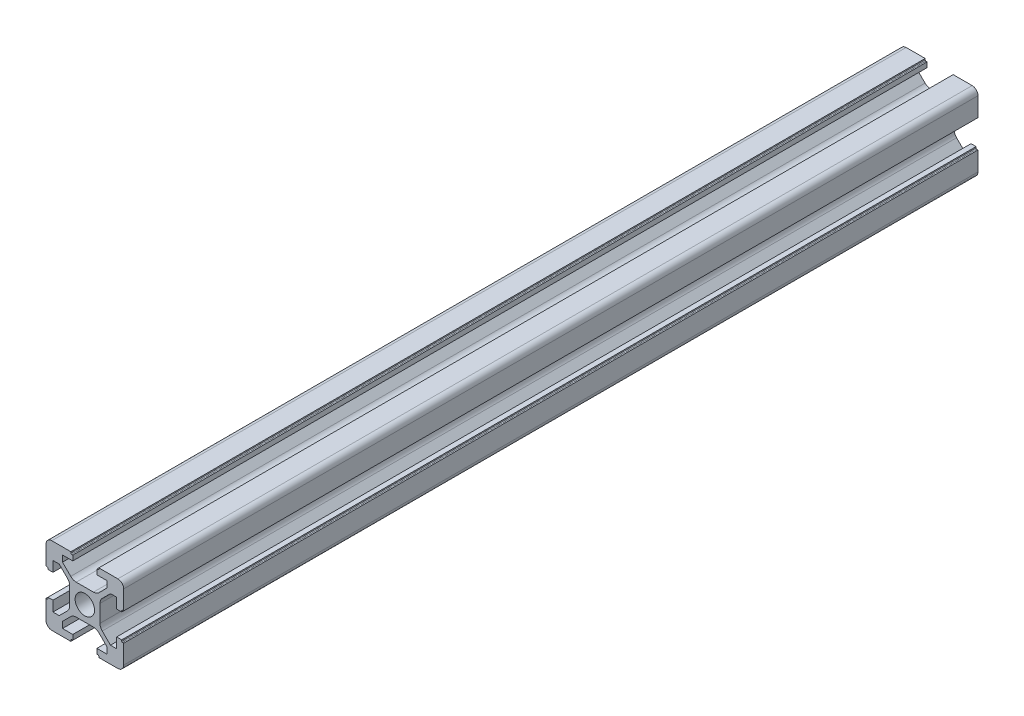
SolidWorks part; units mm, degrees
ref_plane "Alzado" through (0, 0, 0) normal (0, 0, 1) x (1, 0, 0)
ref_plane "Planta" through (0, 0, 0) normal (0, 1, 0) x (1, 0, 0)
ref_plane "Vista lateral" through (0, 0, 0) normal (1, 0, 0) x (0, 0, -1)
sketch "Croquis1" plane through (0, 0, 0) normal (0, 0, 1) x (1, 0, 0)
  line L0 (0, 0) -> (-10, -10) construction
  line L32 (0, 0) -> (-3.9, 0) construction
  line L58 (0, 0) -> (0, -3.9) construction
  line L60 (-4.4858, -3.6373) -> (-6.6, -5.7515)
  line L61 (-6.6, -5.7515) -> (-8.2, -5.7515)
  line L110 (-8.2, -5.7515) -> (-8.2, -3.1)
  line L111 (-8.2, -3.1) -> (-9.5, -3.1)
  line L112 (-9.5, -3.1) -> (-9.5, -3.4)
  line L113 (-9.7, -3.6) -> (-10, -3.6)
  line L114 (-10, -3.6) -> (-10, -8.5)
  line L115 (-3.6373, -4.4858) -> (-5.7515, -6.6)
  line L116 (-5.7515, -6.6) -> (-5.7515, -8.2)
  line L117 (-3.1, -8.2) -> (-3.1, -9.5)
  line L118 (-5.7515, -8.2) -> (-3.1, -8.2)
  line L119 (-3.1, -9.5) -> (-3.4, -9.5)
  line L120 (-3.6, -9.7) -> (-3.6, -10)
  line L121 (-3.6, -10) -> (-8.5, -10)
  line L122 (9.7, -3.6) -> (10, -3.6)
  line L123 (9.5, -3.1) -> (9.5, -3.4)
  line L124 (8.2, -3.1) -> (9.5, -3.1)
  line L125 (3.6, -10) -> (8.5, -10)
  line L126 (3.6, -9.7) -> (3.6, -10)
  line L127 (3.1, -9.5) -> (3.4, -9.5)
  line L128 (5.7515, -8.2) -> (3.1, -8.2)
  line L129 (3.1, -8.2) -> (3.1, -9.5)
  line L130 (5.7515, -6.6) -> (5.7515, -8.2)
  line L131 (3.6373, -4.4858) -> (5.7515, -6.6)
  line L132 (10, -3.6) -> (10, -8.5)
  line L133 (8.2, -5.7515) -> (8.2, -3.1)
  line L134 (6.6, -5.7515) -> (8.2, -5.7515)
  line L135 (4.4858, -3.6373) -> (6.6, -5.7515)
  line L136 (5.7515, 8.2) -> (3.1, 8.2)
  line L137 (3.6, 10) -> (8.5, 10)
  line L138 (-9.7, 3.6) -> (-10, 3.6)
  line L139 (-9.5, 3.1) -> (-9.5, 3.4)
  line L140 (-8.2, 3.1) -> (-9.5, 3.1)
  line L141 (-8.2, 5.7515) -> (-8.2, 3.1)
  line L142 (-6.6, 5.7515) -> (-8.2, 5.7515)
  line L143 (-4.4858, 3.6373) -> (-6.6, 5.7515)
  line L144 (3.1, 8.2) -> (3.1, 9.5)
  line L145 (3.1, 9.5) -> (3.4, 9.5)
  line L146 (3.6, 9.7) -> (3.6, 10)
  line L147 (-3.6, 10) -> (-8.5, 10)
  line L148 (-3.6, 9.7) -> (-3.6, 10)
  line L149 (-3.1, 9.5) -> (-3.4, 9.5)
  line L150 (-5.7515, 8.2) -> (-3.1, 8.2)
  line L151 (-3.1, 8.2) -> (-3.1, 9.5)
  line L152 (-5.7515, 6.6) -> (-5.7515, 8.2)
  line L153 (-3.6373, 4.4858) -> (-5.7515, 6.6)
  line L154 (-10, 3.6) -> (-10, 8.5)
  line L155 (4.4858, 3.6373) -> (6.6, 5.7515)
  line L156 (6.6, 5.7515) -> (8.2, 5.7515)
  line L157 (8.2, 5.7515) -> (8.2, 3.1)
  line L158 (10, 3.6) -> (10, 8.5)
  line L159 (3.6373, 4.4858) -> (5.7515, 6.6)
  line L160 (5.7515, 6.6) -> (5.7515, 8.2)
  line L161 (8.2, 3.1) -> (9.5, 3.1)
  line L162 (9.5, 3.1) -> (9.5, 3.4)
  line L163 (9.7, 3.6) -> (10, 3.6)
  line L164 (-3.9, 2.223) -> (-3.9, -2.223)
  line L165 (-2.223, -3.9) -> (2.223, -3.9)
  line L166 (3.9, -2.223) -> (3.9, 2.223)
  line L167 (2.223, 3.9) -> (-2.223, 3.9)
  circle A2 centre (0, 0) radius 2.5
  arc A3 (8.5, -10) -> (10, -8.5) centre (8.5, -8.5) ccw
  arc A4 (8.5, 10) -> (10, 8.5) centre (8.5, 8.5) cw
  arc A5 (-8.5, 10) -> (-10, 8.5) centre (-8.5, 8.5) ccw
  arc A6 (-10, -8.5) -> (-8.5, -10) centre (-8.5, -8.5) ccw
  arc A7 (-3.9, -2.223) -> (-4.4858, -3.6373) centre (-5.9, -2.223) cw
  arc A8 (4.4858, -3.6373) -> (3.9, -2.223) centre (5.9, -2.223) cw
  arc A9 (4.4858, 3.6373) -> (3.9, 2.223) centre (5.9, 2.223) ccw
  arc A10 (3.6373, 4.4858) -> (2.223, 3.9) centre (2.223, 5.9) cw
  arc A11 (-3.6373, 4.4858) -> (-2.223, 3.9) centre (-2.223, 5.9) ccw
  arc A12 (-4.4858, 3.6373) -> (-3.9, 2.223) centre (-5.9, 2.223) cw
  arc A13 (3.6373, -4.4858) -> (2.223, -3.9) centre (2.223, -5.9) ccw
  arc A14 (-3.6373, -4.4858) -> (-2.223, -3.9) centre (-2.223, -5.9) cw
  arc A15 (-3.4, -9.5) -> (-3.6, -9.7) centre (-3.4, -9.7) ccw
  arc A16 (3.6, -9.7) -> (3.4, -9.5) centre (3.4, -9.7) ccw
  arc A17 (9.7, -3.6) -> (9.5, -3.4) centre (9.7, -3.4) cw
  arc A18 (9.5, 3.4) -> (9.7, 3.6) centre (9.7, 3.4) cw
  arc A19 (3.4, 9.5) -> (3.6, 9.7) centre (3.4, 9.7) ccw
  arc A20 (-9.7, 3.6) -> (-9.5, 3.4) centre (-9.7, 3.4) cw
  arc A21 (-3.6, 9.7) -> (-3.4, 9.5) centre (-3.4, 9.7) ccw
  arc A22 (-9.5, -3.4) -> (-9.7, -3.6) centre (-9.7, -3.4) cw
  point P0 (0, 0)
  point P22 (10, -10)
  point P78 (10, 10)
  point P81 (-10, 10)
  point P90 (-3.9, -3.0515)
  point P93 (3.9, -3.0515)
  point P96 (3.9, 3.0515)
  point P99 (3.0515, 3.9)
  point P102 (-3.0515, 3.9)
  point P105 (-3.9, 3.0515)
  point P108 (3.0515, -3.9)
  point P111 (-3.0515, -3.9)
  point P116 (-3.6, -9.5)
  point P119 (3.6, -9.5)
  point P122 (9.5, -3.6)
  point P125 (9.5, 3.6)
  point P128 (3.6, 9.5)
  point P131 (-9.5, 3.6)
  point P134 (-3.6, 9.5)
  point P137 (-9.5, -3.6)
  dimension "D10" = 20
  dimension "D1" = 5
  dimension "D11" = 1.5
  dimension "D13" = 2
  dimension "D15" = 0.2
  dimension "D2" = 6.2
  dimension "D3" = 7.2
  dimension "D4" = 0.5
  dimension "D5" = 3.4
  dimension "D6" = 11.5029
  dimension "D7" = 6.1
  dimension "D8" = 1.8
  dimension "D9" = 1.2
extrude "Saliente-Extruir1" add sketch "Croquis1" along normal mid plane 220
sketch "Croquis3" [suppressed] plane through (0, 0, 0) normal (0, 0, 1) x (1, 0, 0)
  line L0 (-3.6363, -5.5152) -> (-6.6, -2.5556)
  line L3 (0, 0) -> (-10, 0) construction
  line L5 (-6.6, -2.5556) -> (-8.2, -2.5556)
  line L7 (0, -13.9) -> (0, -6.1) construction
  line L56 (-9.5, -13.1015) -> (-9.5, -13.4015)
  line L57 (-8.2, -13.1015) -> (-9.5, -13.1015)
  line L58 (-8.2, -15.7515) -> (-8.2, -13.1015)
  line L59 (-6.6, -15.7515) -> (-8.2, -15.7515)
  line L60 (-4.4858, -13.6373) -> (-6.6, -15.7515)
  line L61 (-3.9, -7.777) -> (-3.9, -12.223)
  line L62 (-6.6, -4.2515) -> (-4.4868, -6.3618)
  line L63 (-8.2, -4.2515) -> (-6.6, -4.2515)
  line L64 (-8.2, -6.9015) -> (-8.2, -4.2515)
  line L65 (-9.5, -6.9015) -> (-8.2, -6.9015)
  line L66 (-9.5, -6.6015) -> (-9.5, -6.9015)
  line L67 (-10, -6.4015) -> (-9.7, -6.4015)
  line L68 (-5.7515, -16.6) -> (-3.6373, -14.4858)
  line L69 (-5.7515, -18.2) -> (-5.7515, -16.6)
  line L70 (-3.1015, -18.2) -> (-5.7515, -18.2)
  line L71 (-3.1015, -19.5) -> (-3.1015, -18.2)
  line L72 (-3.4015, -19.5) -> (-3.1015, -19.5)
  line L73 (-3.6015, -20) -> (-3.6015, -19.7)
  line L74 (-8.5, -20) -> (-3.6015, -20)
  line L75 (-10, -13.6015) -> (-10, -18.5)
  line L76 (-9.7, -13.6015) -> (-10, -13.6015)
  line L102 (-10, -6.4015) -> (-10, 6.4015)
  line L103 (-8.2, -2.5556) -> (-8.2, 2.5556)
  line L104 (-2.223, -6.1) -> (2.223, -6.1)
  line L105 (-2.223, -13.9) -> (2.223, -13.9)
  line L106 (8.2, -2.5556) -> (8.2, 2.5556)
  line L107 (10, -6.4015) -> (10, 6.4015)
  line L108 (9.7, -13.6015) -> (10, -13.6015)
  line L109 (10, -13.6015) -> (10, -18.5)
  line L110 (8.5, -20) -> (3.6015, -20)
  line L111 (3.6015, -20) -> (3.6015, -19.7)
  line L112 (3.4015, -19.5) -> (3.1015, -19.5)
  line L113 (3.1015, -19.5) -> (3.1015, -18.2)
  line L114 (3.1015, -18.2) -> (5.7515, -18.2)
  line L115 (5.7515, -18.2) -> (5.7515, -16.6)
  line L116 (5.7515, -16.6) -> (3.6373, -14.4858)
  line L117 (10, -6.4015) -> (9.7, -6.4015)
  line L118 (9.5, -6.6015) -> (9.5, -6.9015)
  line L119 (9.5, -6.9015) -> (8.2, -6.9015)
  line L120 (8.2, -6.9015) -> (8.2, -4.2515)
  line L121 (8.2, -4.2515) -> (6.6, -4.2515)
  line L122 (6.6, -4.2515) -> (4.4868, -6.3618)
  line L123 (3.9, -7.777) -> (3.9, -12.223)
  line L124 (4.4858, -13.6373) -> (6.6, -15.7515)
  line L125 (6.6, -15.7515) -> (8.2, -15.7515)
  line L126 (8.2, -15.7515) -> (8.2, -13.1015)
  line L127 (8.2, -13.1015) -> (9.5, -13.1015)
  line L128 (9.5, -13.1015) -> (9.5, -13.4015)
  line L129 (6.6, -2.5556) -> (8.2, -2.5556)
  line L130 (3.6363, -5.5152) -> (6.6, -2.5556)
  line L131 (3.6363, 5.5152) -> (6.6, 2.5556)
  line L132 (6.6, 2.5556) -> (8.2, 2.5556)
  line L133 (9.5, 13.1015) -> (9.5, 13.4015)
  line L134 (8.2, 13.1015) -> (9.5, 13.1015)
  line L135 (8.2, 15.7515) -> (8.2, 13.1015)
  line L136 (6.6, 15.7515) -> (8.2, 15.7515)
  line L137 (4.4858, 13.6373) -> (6.6, 15.7515)
  line L138 (3.9, 7.777) -> (3.9, 12.223)
  line L139 (6.6, 4.2515) -> (4.4868, 6.3618)
  line L140 (8.2, 4.2515) -> (6.6, 4.2515)
  line L141 (8.2, 6.9015) -> (8.2, 4.2515)
  line L142 (9.5, 6.9015) -> (8.2, 6.9015)
  line L143 (9.5, 6.6015) -> (9.5, 6.9015)
  line L144 (10, 6.4015) -> (9.7, 6.4015)
  line L145 (5.7515, 16.6) -> (3.6373, 14.4858)
  line L146 (5.7515, 18.2) -> (5.7515, 16.6)
  line L147 (3.1015, 18.2) -> (5.7515, 18.2)
  line L148 (3.1015, 19.5) -> (3.1015, 18.2)
  line L149 (3.4015, 19.5) -> (3.1015, 19.5)
  line L150 (3.6015, 20) -> (3.6015, 19.7)
  line L151 (8.5, 20) -> (3.6015, 20)
  line L152 (10, 13.6015) -> (10, 18.5)
  line L153 (9.7, 13.6015) -> (10, 13.6015)
  line L154 (-2.223, 13.9) -> (2.223, 13.9)
  line L155 (-2.223, 6.1) -> (2.223, 6.1)
  line L156 (-9.7, 13.6015) -> (-10, 13.6015)
  line L157 (-10, 13.6015) -> (-10, 18.5)
  line L158 (-8.5, 20) -> (-3.6015, 20)
  line L159 (-3.6015, 20) -> (-3.6015, 19.7)
  line L160 (-3.4015, 19.5) -> (-3.1015, 19.5)
  line L161 (-3.1015, 19.5) -> (-3.1015, 18.2)
  line L162 (-3.1015, 18.2) -> (-5.7515, 18.2)
  line L163 (-5.7515, 18.2) -> (-5.7515, 16.6)
  line L164 (-5.7515, 16.6) -> (-3.6373, 14.4858)
  line L165 (-10, 6.4015) -> (-9.7, 6.4015)
  line L166 (-9.5, 6.6015) -> (-9.5, 6.9015)
  line L167 (-9.5, 6.9015) -> (-8.2, 6.9015)
  line L168 (-8.2, 6.9015) -> (-8.2, 4.2515)
  line L169 (-8.2, 4.2515) -> (-6.6, 4.2515)
  line L170 (-6.6, 4.2515) -> (-4.4868, 6.3618)
  line L171 (-3.9, 7.777) -> (-3.9, 12.223)
  line L172 (-4.4858, 13.6373) -> (-6.6, 15.7515)
  line L173 (-6.6, 15.7515) -> (-8.2, 15.7515)
  line L174 (-8.2, 15.7515) -> (-8.2, 13.1015)
  line L175 (-8.2, 13.1015) -> (-9.5, 13.1015)
  line L176 (-9.5, 13.1015) -> (-9.5, 13.4015)
  line L177 (-6.6, 2.5556) -> (-8.2, 2.5556)
  line L178 (-3.6363, 5.5152) -> (-6.6, 2.5556)
  line L179 (0, -10) -> (-9.5607, -19.5607) construction
  circle A8 centre (0, -10) radius 2.5
  arc A20 (-4.4858, -13.6373) -> (-3.9, -12.223) centre (-5.9, -12.223) ccw
  arc A21 (-3.9, -7.777) -> (-4.4868, -6.3618) centre (-5.9, -7.777) ccw
  arc A22 (-9.5, -6.6015) -> (-9.7, -6.4015) centre (-9.7, -6.6015) ccw
  arc A23 (-3.6363, -5.5152) -> (-2.223, -6.1) centre (-2.223, -4.1) ccw
  arc A24 (-2.223, -13.9) -> (-3.6373, -14.4858) centre (-2.223, -15.9) ccw
  arc A25 (-3.4015, -19.5) -> (-3.6015, -19.7) centre (-3.4015, -19.7) ccw
  arc A26 (-10, -18.5) -> (-8.5, -20) centre (-8.5, -18.5) ccw
  arc A27 (-9.7, -13.6015) -> (-9.5, -13.4015) centre (-9.7, -13.4015) ccw
  arc A34 (9.7, -13.6015) -> (9.5, -13.4015) centre (9.7, -13.4015) cw
  arc A35 (10, -18.5) -> (8.5, -20) centre (8.5, -18.5) cw
  arc A36 (3.4015, -19.5) -> (3.6015, -19.7) centre (3.4015, -19.7) cw
  arc A37 (2.223, -13.9) -> (3.6373, -14.4858) centre (2.223, -15.9) cw
  arc A38 (3.6363, -5.5152) -> (2.223, -6.1) centre (2.223, -4.1) cw
  arc A39 (9.5, -6.6015) -> (9.7, -6.4015) centre (9.7, -6.6015) cw
  arc A40 (3.9, -7.777) -> (4.4868, -6.3618) centre (5.9, -7.777) cw
  arc A41 (4.4858, -13.6373) -> (3.9, -12.223) centre (5.9, -12.223) cw
  arc A42 (4.4858, 13.6373) -> (3.9, 12.223) centre (5.9, 12.223) ccw
  arc A43 (3.9, 7.777) -> (4.4868, 6.3618) centre (5.9, 7.777) ccw
  arc A44 (9.5, 6.6015) -> (9.7, 6.4015) centre (9.7, 6.6015) ccw
  arc A45 (3.6363, 5.5152) -> (2.223, 6.1) centre (2.223, 4.1) ccw
  arc A46 (2.223, 13.9) -> (3.6373, 14.4858) centre (2.223, 15.9) ccw
  arc A47 (3.4015, 19.5) -> (3.6015, 19.7) centre (3.4015, 19.7) ccw
  arc A48 (10, 18.5) -> (8.5, 20) centre (8.5, 18.5) ccw
  arc A49 (9.7, 13.6015) -> (9.5, 13.4015) centre (9.7, 13.4015) ccw
  arc A50 (-9.7, 13.6015) -> (-9.5, 13.4015) centre (-9.7, 13.4015) cw
  arc A51 (-10, 18.5) -> (-8.5, 20) centre (-8.5, 18.5) cw
  arc A52 (-3.4015, 19.5) -> (-3.6015, 19.7) centre (-3.4015, 19.7) cw
  arc A53 (-2.223, 13.9) -> (-3.6373, 14.4858) centre (-2.223, 15.9) cw
  arc A54 (-3.6363, 5.5152) -> (-2.223, 6.1) centre (-2.223, 4.1) cw
  arc A55 (-9.5, 6.6015) -> (-9.7, 6.4015) centre (-9.7, 6.6015) cw
  arc A56 (-3.9, 7.777) -> (-4.4868, 6.3618) centre (-5.9, 7.777) cw
  arc A57 (-4.4858, 13.6373) -> (-3.9, 12.223) centre (-5.9, 12.223) cw
  circle A58 centre (0, 10) radius 2.5
  point P59 (8.2, 0)
  point P63 (8.2, 0)
  point P159 (10, 0)
  point P160 (-8.2, 0)
  point P174 (-8.2, 0)
  point P190 (-3.9, -10)
  point P193 (0, -10)
  dimension "D8" = 2
  dimension "D9" = 1.5
  dimension "D11" = 5
  dimension "D13" = 0.2
  dimension "D1" = 40
  dimension "D2" = 11.5
  dimension "D3" = 6.2
  dimension "D4" = 1.8
  dimension "D5" = 0.5
  dimension "D6" = 3.4
  dimension "D7" = 20
  dimension "D10" = 1.2
  dimension "D12" = 7.8
  dimension "D14" = 20
extrude "Saliente-Extruir3" [suppressed] add sketch "Croquis3" along normal mid plane 350 separate body
